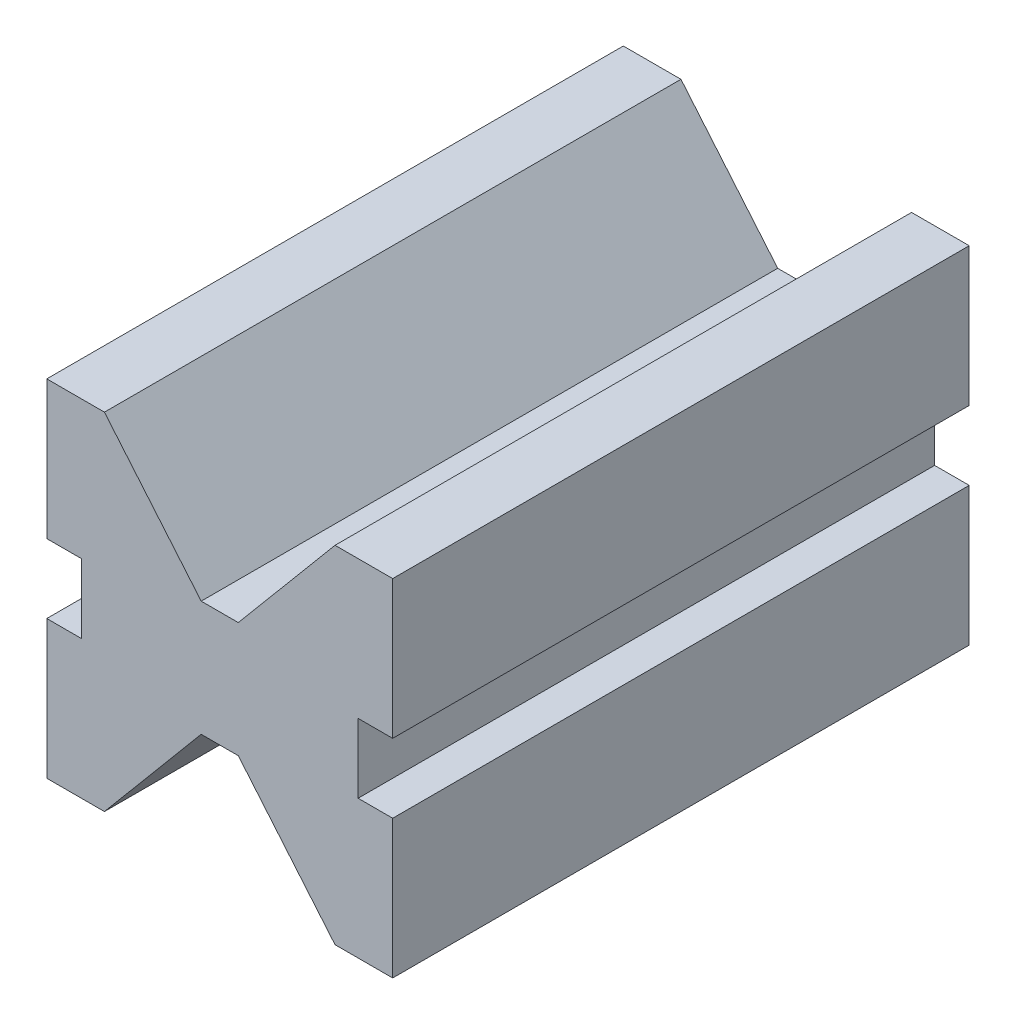
SolidWorks part; units mm, degrees
material "3003 Alloy"
ref_plane "Front Plane" through (0, 0, 0) normal (0, 0, 1) x (1, 0, 0)
ref_plane "Top Plane" through (0, 0, 0) normal (0, 1, 0) x (1, 0, 0)
ref_plane "Right Plane" through (0, 0, 0) normal (1, 0, 0) x (0, 0, -1)
sketch "Sketch1" plane through (0, 0, 0) normal (0, 0, 1) x (1, 0, 0)
  line L0 (20, -30) -> (3.218, -10)
  line L1 (-30, 30) -> (-20, 30)
  line L2 (-30, 30) -> (-30, 6)
  line L3 (-30, -30) -> (-20, -30)
  line L4 (30, 30) -> (30, 6)
  line L5 (-30, 30) -> (30, -30) construction
  line L6 (-30, -30) -> (30, 30) construction
  line L7 (3.218, -10) -> (-3.218, -10)
  line L8 (-3.218, -10) -> (-20, -30)
  line L9 (-20, -30) -> (-30, -30)
  line L10 (24, 0) -> (-30, 0) construction
  line L11 (30, -6) -> (24, -6)
  line L12 (24, -6) -> (24, 6)
  line L13 (24, 6) -> (30, 6)
  line L14 (0, 10) -> (0, 0) construction
  line L15 (-3.218, 10) -> (-20, 30)
  line L16 (3.218, 10) -> (-3.218, 10)
  line L17 (20, 30) -> (3.218, 10)
  line L18 (-24, 6) -> (-30, 6)
  line L19 (-30, -6) -> (-24, -6)
  line L20 (-24, -6) -> (-24, 6)
  line L21 (-30, -6) -> (-30, -30)
  line L22 (20, -30) -> (30, -30)
  line L23 (20, -30) -> (-20, -30) construction
  line L24 (20, 30) -> (30, 30)
  line L25 (30, -6) -> (30, -30)
  point P0 (0, 0)
  point P22 (27, 6)
  dimension "D1" = 60
  dimension "D2" = 60
  dimension "D3" = 50
  dimension "D4" = 10
  dimension "D5" = 10
  dimension "D6" = 20
  dimension "D9" = 6
extrude "Boss-Extrude1" add sketch "Sketch1" along normal mid plane 100 contours L25 L11 L12 L13 L4 L24 L17 L16 L15 L1 L2 L18 L20 L19 L21 L3 L8 L7 L0 L22
